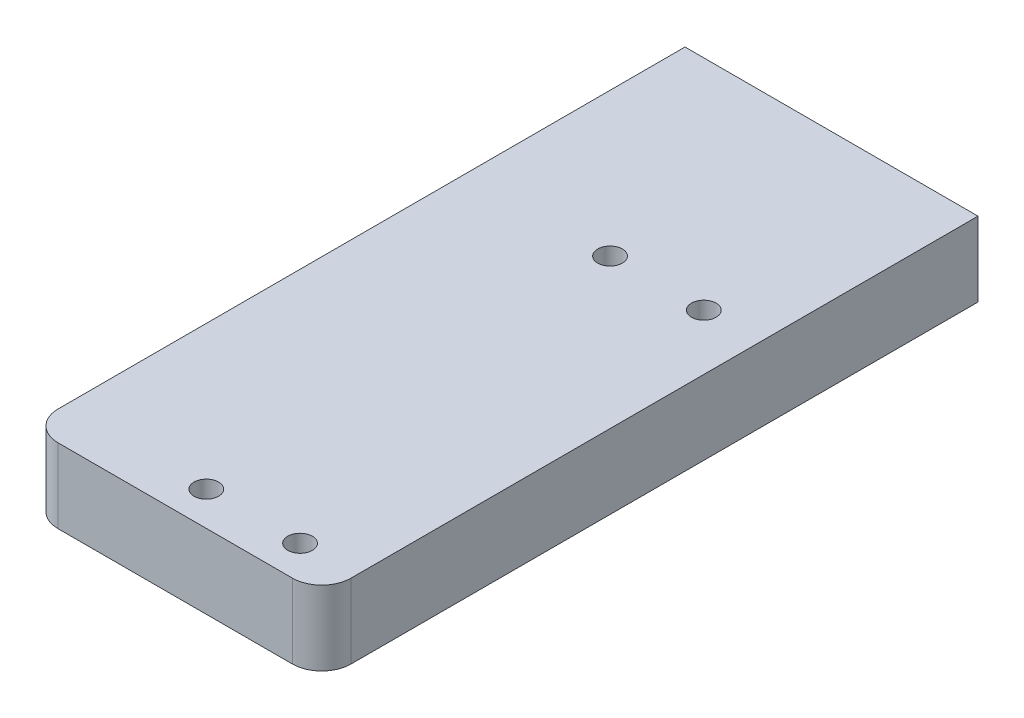
SolidWorks part; units mm, degrees
ref_plane "Front Plane" through (0, 0, 0) normal (0, 0, 1) x (1, 0, 0)
ref_plane "Top Plane" through (0, 0, 0) normal (0, 1, 0) x (1, 0, 0)
ref_plane "Right Plane" through (0, 0, 0) normal (1, 0, 0) x (0, 0, -1)
sketch "Sketch12" plane through (0, 0, 0) normal (0, 0, 1) x (1, 0, 0)
  line L1 (-25, -6.35) -> (25, -6.35)
  line L2 (-25, -6.35) -> (-25, 6.35)
  line L3 (-25, 6.35) -> (25, 6.35)
  line L4 (25, -6.35) -> (25, 6.35)
  line L5 (0, 6.35) -> (0, -6.35) construction
  line L6 (-25, 0) -> (25, 0) construction
  point P0 (0, 0)
  dimension "D1" = 12.7
  dimension "D2" = 50
extrude "Boss-Extrude1" add sketch "Sketch12" along normal blind 112
sketch "Sketch13" plane through (0, 0, 0) normal (0, 0, -1) x (-1, 0, 0)
  line L0 (-25, 0) -> (25, 0) construction
  line L1 (-25, -6.35) -> (-25, 6.35) construction
  line L2 (25, 6.35) -> (25, -6.35) construction
  point P6 (0, 0)
  point P7 (-17.5, 0)
  point P9 (17.5, 0)
  dimension "D1" = 7.5
  dimension "D2" = 7.5
  dimension "D3" = 35
hole_wizard "M5x0.8 Tapped Hole2" positions "Sketch14" profile "Sketch15" tap size "M5x0.8" standard "ANSI Metric"
sketch "Sketch14" plane through (0, 0, 0) normal (0, 0, -1) x (-1, 0, 0)
  point P0 (-17.5, 0)
  point P3 (0, 0)
  point P6 (17.5, 0)
sketch "Sketch15" plane through (17.5, 0, 0) normal (1, 0, 0) x (0, 1, 0)
  line L0 (0, 0) -> (0, 15.6618)
  line L1 (0, 15.6618) -> (2.1, 14.4)
  line L2 (2.1, 14.4) -> (2.1, 0)
  line L5 (2.1, 0) -> (0, 0)
  line L10 (0, 15.6618) -> (-2.1, 14.4) construction
  line L11 (0, -6.35) -> (0, 107.95) construction
  dimension "Tap Drill Dia." = 4.2
  dimension "Tap Drill Depth" = 14.4
  dimension "Drill Angle" = 118
cosmetic thread "Hole Thread1" parameters "D1"=12, "D2"=5
cosmetic thread "Hole Thread2" parameters "D1"=12, "D2"=5
cosmetic thread "Hole Thread3" parameters "D1"=12, "D2"=5
sketch "Sketch16" plane through (0, 6.35, 0) normal (0, 1, 0) x (1, 0, 0)
  line L0 (15.5, -37.3) -> (-0.5, -37.3) construction
  line L1 (-0.5, -37.3) -> (-0.5, -106.2) construction
  line L2 (-0.5, -106.2) -> (15.5, -106.2) construction
  line L3 (15.5, -106.2) -> (15.5, -37.3) construction
  line L4 (25, 0) -> (-25, 0) construction
  line L5 (25, -112) -> (25, 0) construction
  circle A0 centre (15.5, -37.3) radius 2.75 construction
  circle A1 centre (-0.5, -37.3) radius 2.75 construction
  circle A2 centre (15.5, -106.2) radius 2.75 construction
  circle A3 centre (-0.5, -106.2) radius 2.75 construction
  dimension "D1" = 37.3
  dimension "D4" = 5.5
  dimension "D2" = 68.9
  dimension "D3" = 16
  dimension "D5" = 9.5
hole_wizard "M5x0.8 Tapped Hole3" positions "Sketch17" profile "Sketch18" tap size "M5x0.8" standard "ANSI Metric" end condition through all
sketch "Sketch17" plane through (0, 6.35, 0) normal (0, 1, 0) x (1, 0, 0)
  point P0 (-0.5, -37.3)
  point P3 (15.5, -37.3)
  point P6 (15.5, -106.2)
  point P9 (-0.5, -106.2)
sketch "Sketch18" plane through (-0.5, 6.35, 37.3) normal (1, 0, 0) x (0, 0, 1)
  line L0 (0, 0) -> (0, 12.7)
  line L1 (0, 12.7) -> (2.1, 12.7)
  line L2 (2.1, 12.7) -> (2.1, 0)
  line L5 (2.1, 0) -> (0, 0)
  line L11 (0, -6.35) -> (0, 107.95) construction
  dimension "Thru Tap Drill Dia." = 4.2
  dimension "Thru Tap Drill Depth" = 12.7
cosmetic thread "Hole Thread4" parameters "D2"=5
cosmetic thread "Hole Thread5" parameters "D2"=5
cosmetic thread "Hole Thread6" parameters "D2"=5
cosmetic thread "Hole Thread7" parameters "D2"=5
sketch "Sketch19" plane through (0, -6.35, 0) normal (0, 1, 0) x (1, 0, 0)
  line L0 (25, -112) -> (25, 0) construction
  line L1 (-17, -45.3) -> (17, -45.3)
  line L2 (-17, -45.3) -> (-17, -98.2)
  line L3 (-17, -98.2) -> (17, -98.2)
  line L4 (17, -45.3) -> (17, -98.2)
  line L5 (0, -98.2) -> (0, -45.3) construction
  line L6 (-17, -71.75) -> (17, -71.75) construction
  line L7 (-25, -112) -> (-25, 0) construction
  circle A0 centre (15.5, -37.3) radius 2.1 construction
  circle A1 centre (15.5, -106.2) radius 2.1 construction
  point P148 (0, -71.75)
  dimension "D1" = 8
  dimension "D2" = 8
  dimension "D3" = 8
  dimension "D4" = 8
extrude "Cut-Extrude1" cut sketch "Sketch19" along normal blind 9.7
fillet "Fillet1" radius 5 6 edges at (-17, -1.5, 98.2) (17, -1.5, 98.2) (17, -1.5, 45.3) (-17, -1.5, 45.3) (-25, 0, 112) (25, 0, 112)
